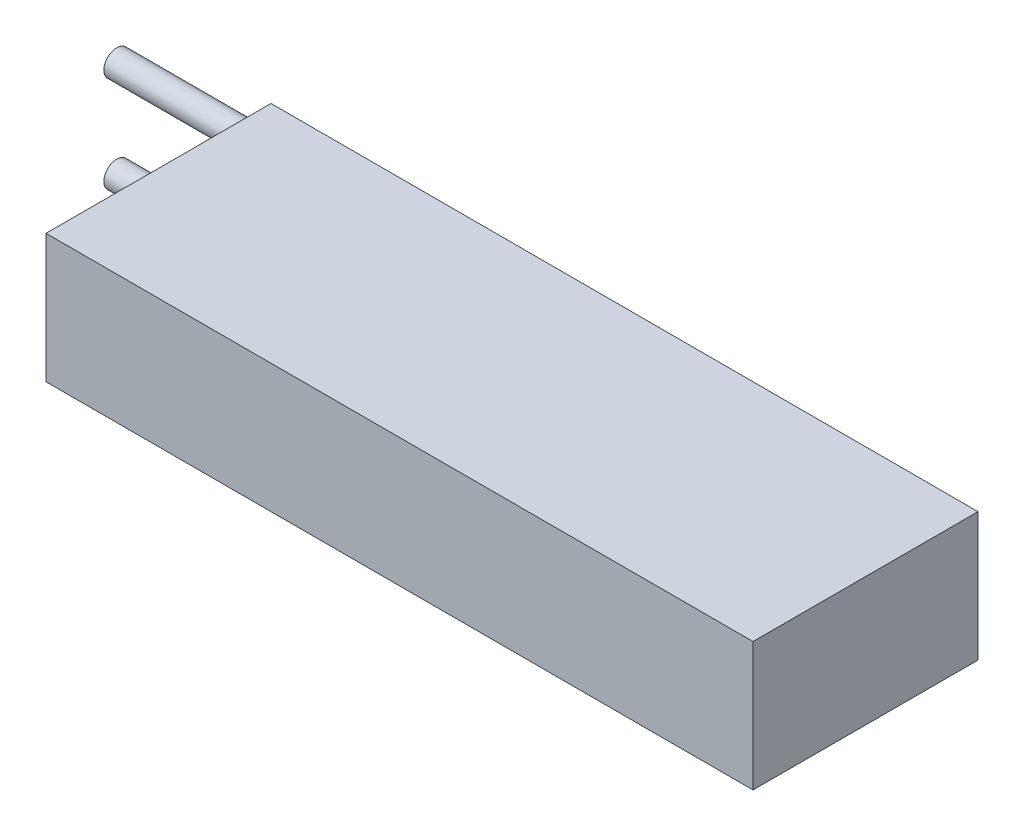
SolidWorks part; units mm, degrees
ref_plane "Front Plane" through (0, 0, 0) normal (0, 0, 1) x (1, 0, 0)
ref_plane "Top Plane" through (0, 0, 0) normal (0, 1, 0) x (1, 0, 0)
ref_plane "Right Plane" through (0, 0, 0) normal (1, 0, 0) x (0, 0, -1)
sketch "Sketch1" plane through (0, 0, 0) normal (0, 1, 0) x (1, 0, 0)
  line L1 (0, 0) -> (110, 0)
  line L2 (0, 0) -> (0, 35)
  line L3 (0, 35) -> (110, 35)
  line L4 (110, 0) -> (110, 35)
  dimension "D1" = 110
  dimension "D2" = 35
extrude "Boss-Extrude1" add sketch "Sketch1" along normal blind 20
sketch "Sketch2" plane through (0, 0, 0) normal (-1, 0, 0) x (0, 0, 1)
  line L0 (-31, 17.5) -> (-31, 2.5) construction
  line L1 (-35, 20) -> (-35, 0) construction
  line L2 (-31, 10) -> (-35, 10) construction
  circle A0 centre (-31, 17.5) radius 2
  circle A1 centre (-31, 2.5) radius 2
  dimension "D1" = 4
  dimension "D2" = 4
  dimension "D3" = 4
  dimension "D4" = 15
extrude "Boss-Extrude2" add sketch "Sketch2" along normal blind 20
